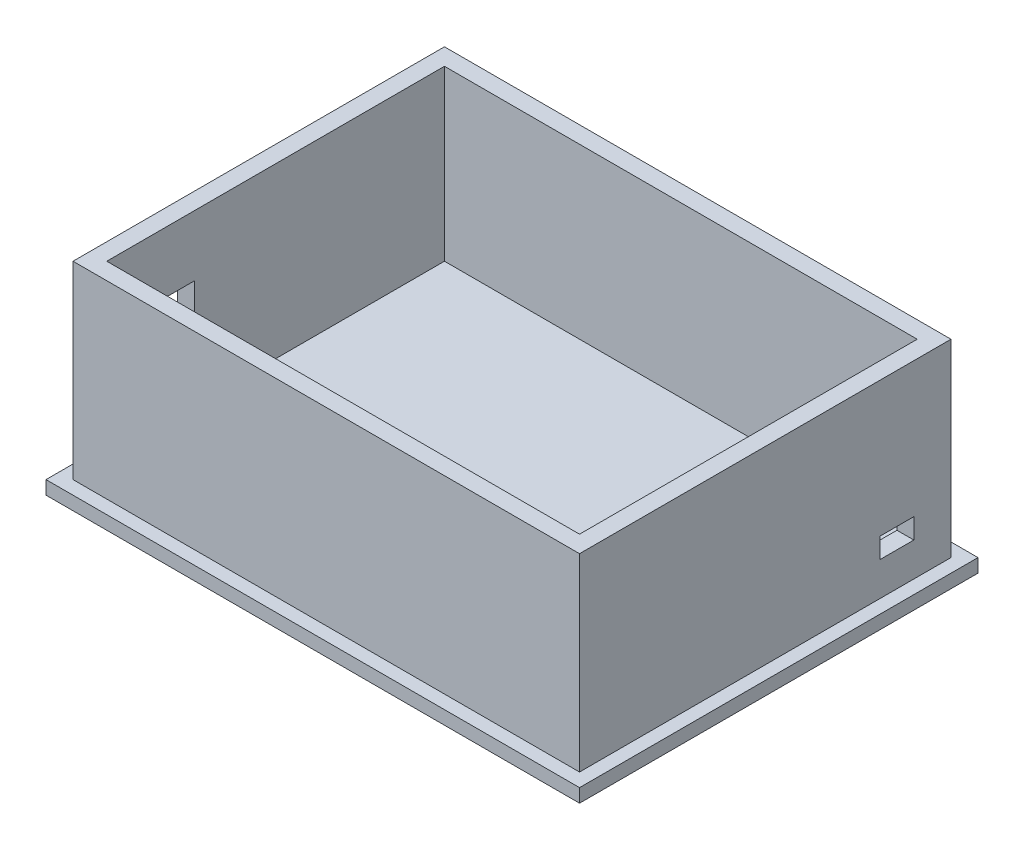
SolidWorks part; units mm, degrees
ref_plane "Front Plane" through (0, 0, 0) normal (0, 0, 1) x (1, 0, 0)
ref_plane "Top Plane" through (0, 0, 0) normal (0, 1, 0) x (1, 0, 0)
ref_plane "Right Plane" through (0, 0, 0) normal (1, 0, 0) x (0, 0, -1)
sketch "Sketch1" plane through (0, 0, 0) normal (0, 1, 0) x (1, 0, 0)
  line L1 (0, 0) -> (95.25, 0)
  line L2 (0, 0) -> (0, 69.85)
  line L3 (0, 69.85) -> (95.25, 69.85)
  line L4 (95.25, 0) -> (95.25, 69.85)
  dimension "D1" = 69.85
  dimension "D2" = 95.25
extrude "Boss-Extrude1" add sketch "Sketch1" along normal blind 38.1
sketch "Sketch2" plane through (0, 38.1, 0) normal (0, 1, 0) x (1, 0, 0)
  line L0 (0, 69.85) -> (0, 0) construction
  line L1 (3.175, 66.675) -> (92.075, 66.675)
  line L2 (3.175, 66.675) -> (3.175, 3.175)
  line L3 (3.175, 3.175) -> (92.075, 3.175)
  line L4 (92.075, 66.675) -> (92.075, 3.175)
  line L5 (95.25, 69.85) -> (0, 69.85) construction
  point P4 (0, 34.925)
  point P5 (47.625, 69.85)
  point P8 (47.625, 66.675)
  point P11 (3.175, 34.925)
  point P12 (0, 0)
  point P13 (0, 0)
  dimension "D1" = 3.175
  dimension "D2" = 3.175
extrude "Cut-Extrude1" cut sketch "Sketch2" against normal offset from surface (31.75 mm away) 6.35 up to face at (47.625, 0, -34.925)
sketch "Sketch3" plane through (95.25, 0, 0) normal (1, 0, 0) x (0, 0, -1)
  line L0 (3.175, 6.35) -> (66.675, 6.35) construction
  line L1 (62.865, 12.7) -> (56.515, 12.7)
  line L2 (62.865, 12.7) -> (62.865, 8.89)
  line L3 (62.865, 8.89) -> (56.515, 8.89)
  line L4 (56.515, 12.7) -> (56.515, 8.89)
  line L5 (66.675, 6.35) -> (66.675, 38.1) construction
  dimension "D1" = 3.81
  dimension "D2" = 6.35
  dimension "D3" = 2.54
  dimension "D4" = 3.81
extrude "Cut-Extrude2" cut sketch "Sketch3" against normal up to next contours L4 L3 L2 L1
sketch "Sketch4" plane through (0, 0, 0) normal (-1, 0, 0) x (0, 0, 1)
  line L0 (-66.675, 6.35) -> (-3.175, 6.35) construction
  line L1 (-6.985, 26.67) -> (-19.685, 26.67)
  line L2 (-6.985, 26.67) -> (-6.985, 21.59)
  line L3 (-6.985, 21.59) -> (-19.685, 21.59)
  line L4 (-19.685, 26.67) -> (-19.685, 21.59)
  line L5 (-3.175, 6.35) -> (-3.175, 38.1) construction
  dimension "D1" = 5.08
  dimension "D2" = 15.24
  dimension "D3" = 12.7
  dimension "D4" = 3.81
extrude "Cut-Extrude3" cut sketch "Sketch4" against normal up to next contours L4 L3 L2 L1
sketch "Sketch5" plane through (0, 0, 0) normal (0, -1, 0) x (1, 0, 0)
  line L8 (-2.54, 2.54) -> (-2.54, -72.39)
  line L9 (-2.54, -72.39) -> (97.79, -72.39)
  line L10 (97.79, -72.39) -> (97.79, 2.54)
  line L11 (97.79, 2.54) -> (-2.54, 2.54)
  line L12 (-2.54, 2.54) -> (-2.54, -72.39)
  line L13 (-2.54, -72.39) -> (97.79, -72.39)
  line L14 (97.79, -72.39) -> (97.79, 2.54)
  line L15 (97.79, 2.54) -> (-2.54, 2.54)
  dimension "D1" = 2.54
extrude "Boss-Extrude2" add sketch "Sketch5" against normal blind 2.54
